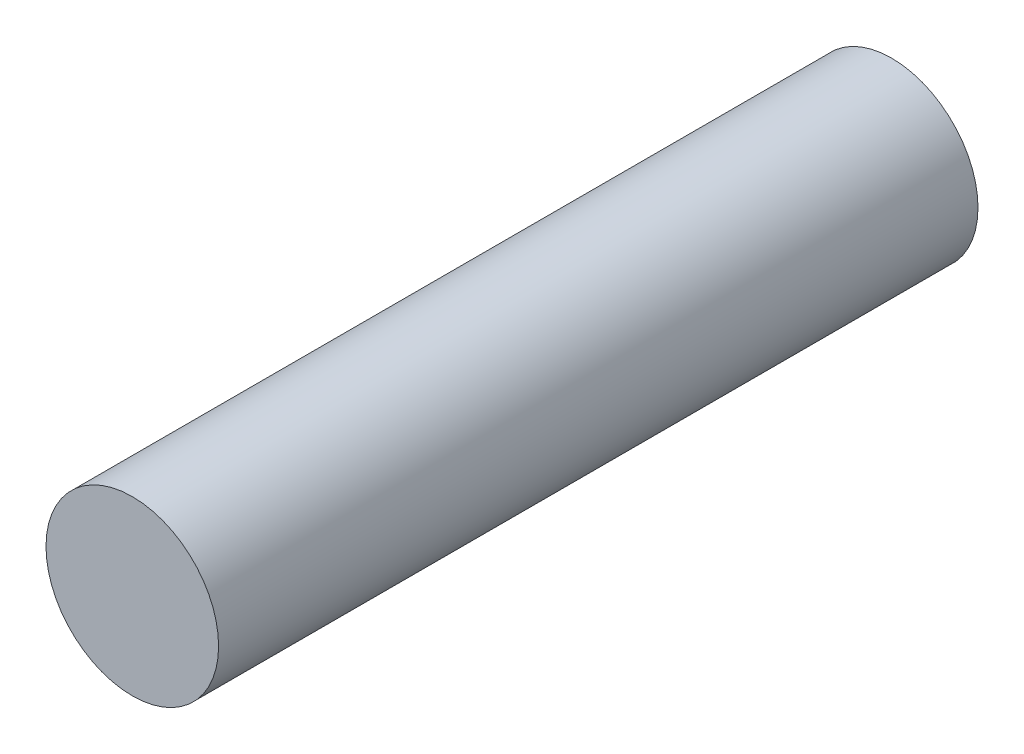
SolidWorks part; units mm, degrees
ref_plane "Front Plane" through (0, 0, 0) normal (0, 0, 1) x (1, 0, 0)
ref_plane "Top Plane" through (0, 0, 0) normal (0, 1, 0) x (1, 0, 0)
ref_plane "Right Plane" through (0, 0, 0) normal (1, 0, 0) x (0, 0, -1)
sketch "Sketch1" plane through (0, 0, 0) normal (0, 0, 1) x (1, 0, 0)
  circle A0 centre (0, 0) radius 2.5
  dimension "D1" = 5
extrude "Boss-Extrude2" add sketch "Sketch1" along normal blind 22
